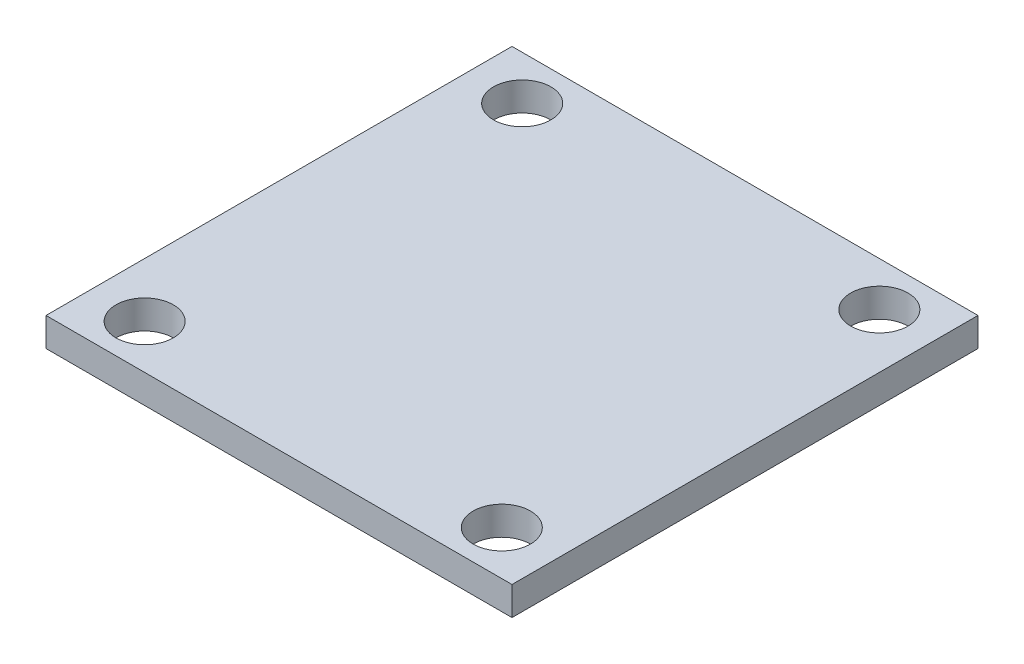
SolidWorks part; units mm, degrees
ref_plane "Front Plane" through (0, 0, 0) normal (0, 0, 1) x (1, 0, 0)
ref_plane "Top Plane" through (0, 0, 0) normal (0, 1, 0) x (1, 0, 0)
ref_plane "Right Plane" through (0, 0, 0) normal (1, 0, 0) x (0, 0, -1)
sketch "Sketch1" plane through (0, 0, 0) normal (0, 1, 0) x (1, 0, 0)
  line L1 (13, -13) -> (-13, -13)
  line L2 (13, -13) -> (13, 13)
  line L3 (13, 13) -> (-13, 13)
  line L4 (-13, -13) -> (-13, 13)
  line L5 (13, -13) -> (-13, 13) construction
  line L6 (13, 13) -> (-13, -13) construction
  point P0 (0, 0)
  dimension "D1" = 26
  dimension "D2" = 26
extrude "Boss-Extrude1" add sketch "Sketch1" along normal blind 1.6
sketch "Sketch3" plane through (0, 1.6, 0) normal (0, 1, 0) x (1, 0, 0)
  line L1 (9.9638, -10.5328) -> (-9.9638, -10.5328) construction
  line L2 (9.9638, -10.5328) -> (9.9638, 10.5328) construction
  line L3 (9.9638, 10.5328) -> (-9.9638, 10.5328) construction
  line L4 (-9.9638, -10.5328) -> (-9.9638, 10.5328) construction
  line L5 (9.9638, -10.5328) -> (-9.9638, 10.5328) construction
  line L6 (9.9638, 10.5328) -> (-9.9638, -10.5328) construction
  circle A0 centre (-9.9638, 10.5328) radius 1.6
  circle A1 centre (-9.9638, -10.5328) radius 1.6
  circle A2 centre (9.9638, 10.5328) radius 1.6
  circle A3 centre (9.9638, -10.5328) radius 1.6
  point P0 (0, 0)
  dimension "D1" = 3.2
extrude "Cut-Extrude1" cut sketch "Sketch3" against normal blind 1.6
